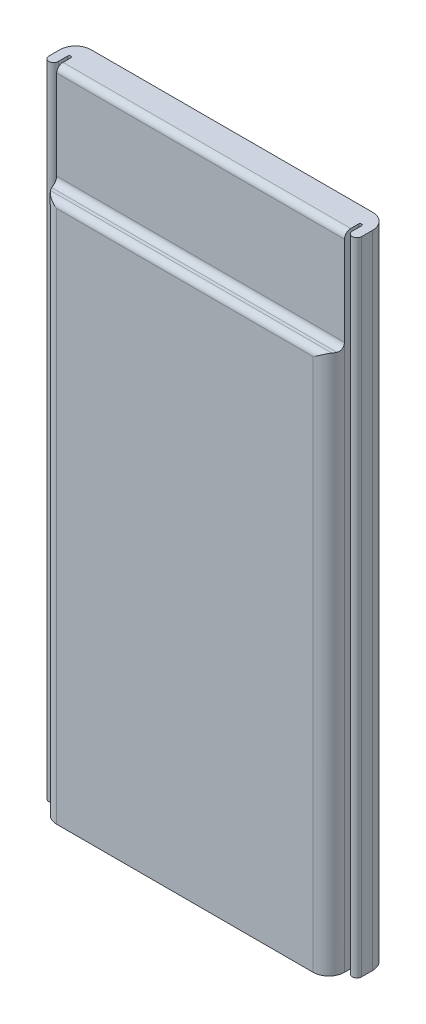
SolidWorks part; units mm, degrees
ref_plane "Front" through (0, 0, 0) normal (0, 0, 1) x (1, 0, 0)
ref_plane "Top" through (0, 0, 0) normal (0, 1, 0) x (1, 0, 0)
ref_plane "Right" through (0, 0, 0) normal (1, 0, 0) x (0, 0, -1)
sketch "Эскиз1" plane through (0, 0, 0) normal (0, 1, 0) x (1, 0, 0)
  line L0 (-9, 0) -> (9, 0)
  line L1 (-8.2, -3) -> (8.2, -3)
  line L2 (-10, -1) -> (-10, -1.7)
  line L3 (10, -1) -> (10, -1.7)
  line L4 (-9.2, -2) -> (-9.2, -1.1)
  line L5 (9.2, -1.1) -> (9.2, -2)
  line L6 (9.4, -1.7) -> (9.4, -1.1)
  line L7 (-9.4, -1.7) -> (-9.4, -1.1)
  arc A0 (-9, 0) -> (-10, -1) centre (-9, -1) ccw
  arc A1 (9, 0) -> (10, -1) centre (9, -1) cw
  arc A2 (-9.2, -2) -> (-8.2, -3) centre (-8.2, -2) ccw
  arc A3 (9.2, -2) -> (8.2, -3) centre (8.2, -2) cw
  arc A4 (10, -1.7) -> (9.4, -1.7) centre (9.7, -1.7) cw
  arc A5 (9.2, -1.1) -> (9.4, -1.1) centre (9.3, -1.1) cw
  arc A6 (-10, -1.7) -> (-9.4, -1.7) centre (-9.7, -1.7) ccw
  arc A7 (-9.2, -1.1) -> (-9.4, -1.1) centre (-9.3, -1.1) ccw
  point P20 (9.3, -1)
  point P21 (9.7, -2)
  point P27 (-9.3, -1)
  point P28 (-9.7, -2)
  dimension "D1" = 20
  dimension "D3" = 1
  dimension "D4" = 1
  dimension "D5" = 0.3
  dimension "D6" = 0.1
  dimension "D2" = 3
extrude "Бобышка-Вытянуть1" add sketch "Эскиз1" along normal mid plane 41
sketch "Эскиз2" plane through (0, 0, 0) normal (1, 0, 0) x (0, 0, -1)
  line L0 (-2, 20.1) -> (-2, 14.4)
  line L1 (-2.4, 14) -> (-2.6, 14)
  line L2 (-3, 20.5) -> (-3, 13.6)
  line L3 (-3, 20.5) -> (-3, -20.5) construction
  line L6 (-3, 20.5) -> (-1.6, 20.5)
  line L7 (0, 20.5) -> (-1, 20.5) construction
  arc A0 (-2, 14.4) -> (-2.4, 14) centre (-2.4, 14.4) cw
  arc A1 (-2.6, 14) -> (-3, 13.6) centre (-2.6, 13.6) ccw
  arc A2 (-1.6, 20.5) -> (-2, 20.1) centre (-1.6, 20.1) ccw
  dimension "D1" = 0.4
  dimension "D2" = 2
  dimension "D3" = 6.5
extrude "Вырез-Вытянуть1" cut sketch "Эскиз2" against normal up to next and the other way up to next
